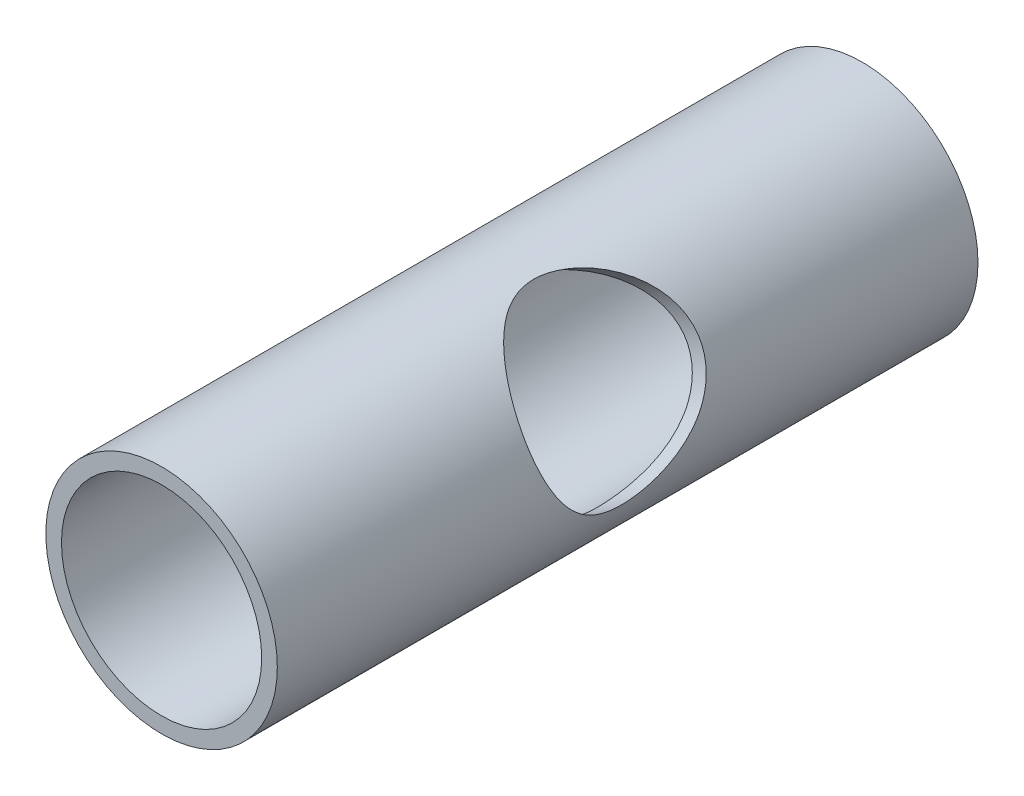
SolidWorks part; units mm, degrees
material "1060 Alloy"
ref_plane "Front Plane" through (0, 0, 0) normal (0, 0, 1) x (1, 0, 0)
ref_plane "Top Plane" through (0, 0, 0) normal (0, 1, 0) x (1, 0, 0)
ref_plane "Right Plane" through (0, 0, 0) normal (1, 0, 0) x (0, 0, -1)
sketch "Sketch1" plane through (0, 0, 0) normal (0, 0, 1) x (1, 0, 0)
  circle A0 centre (0, 0) radius 185
  circle A1 centre (0, 0) radius 160
extrude "Boss-Extrude1" add sketch "Sketch1" along normal blind 1120
sketch "Sketch3" plane through (0, 0, 1120) normal (0, 0, 1) x (1, 0, 0)
  line L0 (0, 0) -> (0, 185)
  line L1 (0, 0) -> (160.2147, 92.5)
  circle A0 centre (0, 0) radius 185 construction
  dimension "D1" = 60
ref_plane "Plane1" through (160.2147, 92.5, 1120) normal (0.866, 0.5, 0) x (0, 0, -1)
sketch "Sketch4" plane through (160.2147, 92.5, 1120) normal (0.866, 0.5, 0) x (0, 0, -1)
  line L0 (0, 0) -> (1120, 0)
  circle A0 centre (560, 0) radius 140
  dimension "D1" = 280
extrude "Cut-Extrude1" cut sketch "Sketch4" against normal blind 200 contours A0
